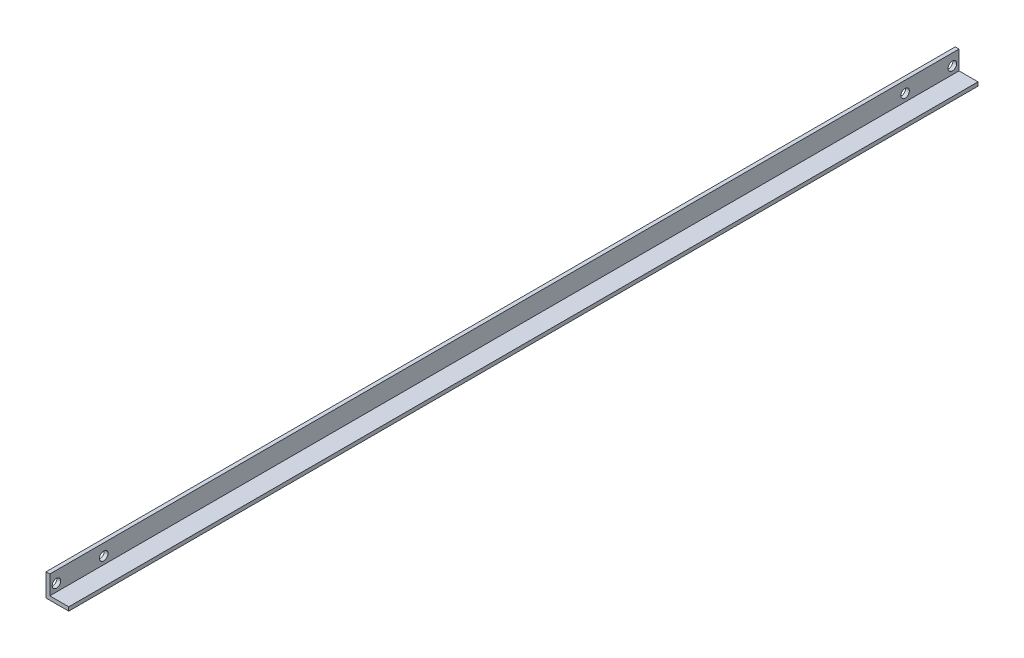
SolidWorks part; units mm, degrees
ref_plane "Front Plane" through (0, 0, 0) normal (0, 0, 1) x (1, 0, 0)
ref_plane "Top Plane" through (0, 0, 0) normal (0, 1, 0) x (1, 0, 0)
ref_plane "Right Plane" through (0, 0, 0) normal (1, 0, 0) x (0, 0, -1)
sketch "Sketch1" plane through (0, 0, 0) normal (0, 0, 1) x (1, 0, 0)
  line L0 (0, 0) -> (19.05, 0)
  line L1 (19.05, 0) -> (19.05, 3.175)
  line L2 (19.05, 3.175) -> (3.175, 3.175)
  line L3 (3.175, 3.175) -> (3.175, 19.05)
  line L4 (3.175, 19.05) -> (0, 19.05)
  line L5 (0, 19.05) -> (0, 0)
  dimension "D1" = 19.05
  dimension "D3" = 3.175
  dimension "D4" = 19.05
extrude "Boss-Extrude1" add sketch "Sketch1" along normal blind 762
hole_wizard "9/32 (0.28125) Diameter Hole1" positions "3DSketch1" profile "Sketch2" hole size "9/32" standard "Ansi Inch" end condition through all
sketch3d "3DSketch1"
  line L5 (0, 19.05, 0) -> (0, 0, 0) construction
  line L7 (0, 9.525, 0) -> (0, 9.525, 762) construction
  line L9 (0, 0, 762) -> (0, 0, 0) construction
  line L10 (0, 19.05, 762) -> (0, 0, 762) construction
  line L11 (0, 9.525, 381) -> (0, -61.5173, 381) construction
  point P39 (0, 9.525, 5.588)
  point P42 (0, 9.525, 45.212)
  point P48 (0, 9.525, 716.787)
  point P50 (0, 9.525, 756.412)
  dimension "D1" = 9.525
  dimension "D3" = 39.624
  dimension "D2" = 375.412
  dimension "D4" = 39.625
  dimension "D5" = 750.824
sketch "Sketch2" plane through (0, 9.525, 5.588) normal (0, 1, 0) x (0, 0, 1)
  line L0 (0, 0) -> (0, 19.05)
  line L1 (0, 19.05) -> (3.5719, 19.05)
  line L2 (3.5719, 19.05) -> (3.5719, 0)
  line L5 (3.5719, 0) -> (0, 0)
  line L11 (0, -6.35) -> (0, 107.95) construction
  dimension "Thru Hole Dia." = 7.1437
  dimension "Thru Hole Depth" = 19.05
equation "\"D2@3DSketch1\" = \"D5@3DSketch1\"/2"
